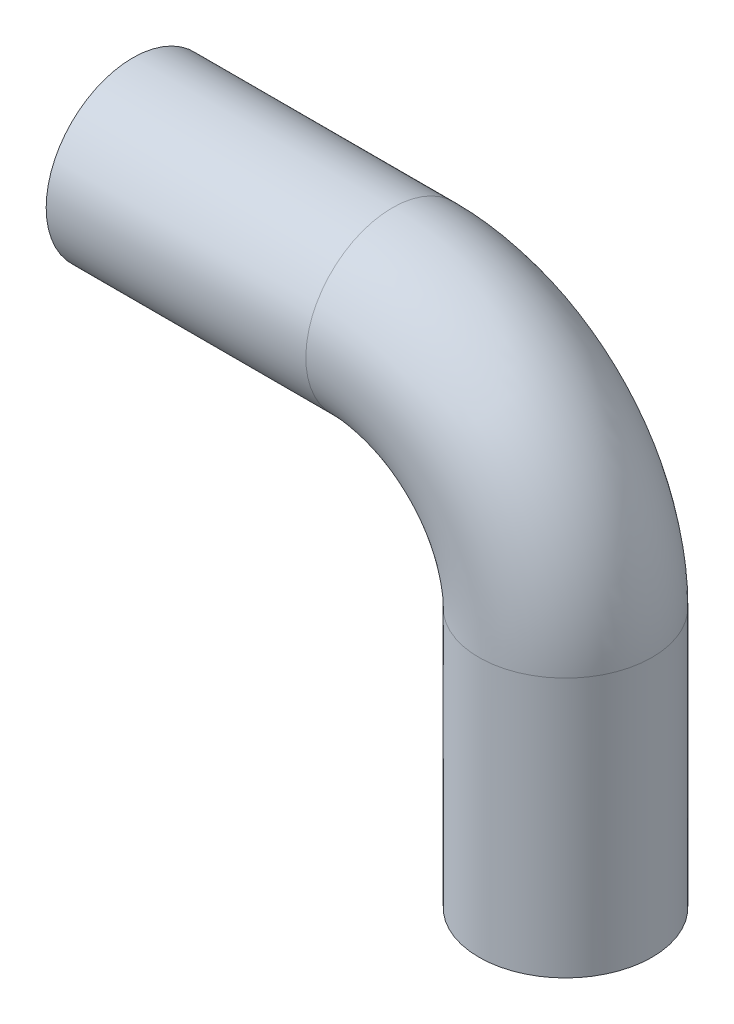
SolidWorks part; units mm, degrees
ref_plane "Front Plane" through (0, 0, 0) normal (0, 0, 1) x (1, 0, 0)
ref_plane "Top Plane" through (0, 0, 0) normal (0, 1, 0) x (1, 0, 0)
ref_plane "Right Plane" through (0, 0, 0) normal (1, 0, 0) x (0, 0, -1)
sketch "Sketch1" plane through (0, 0, 0) normal (0, 0, 1) x (1, 0, 0)
  line L0 (0, 0) -> (30, 0)
  line L1 (50, -20) -> (50, -50)
  arc A0 (50, -20) -> (30, 0) centre (30, -20) ccw
  point P6 (50, 0)
  dimension "D3" = 20
  dimension "D1" = 50
  dimension "D2" = 50
sweep "Sweep1" add path "Sketch1" circular profile diameter 20 parameters "D3"=20
shell "Shell4" thickness 2.3
